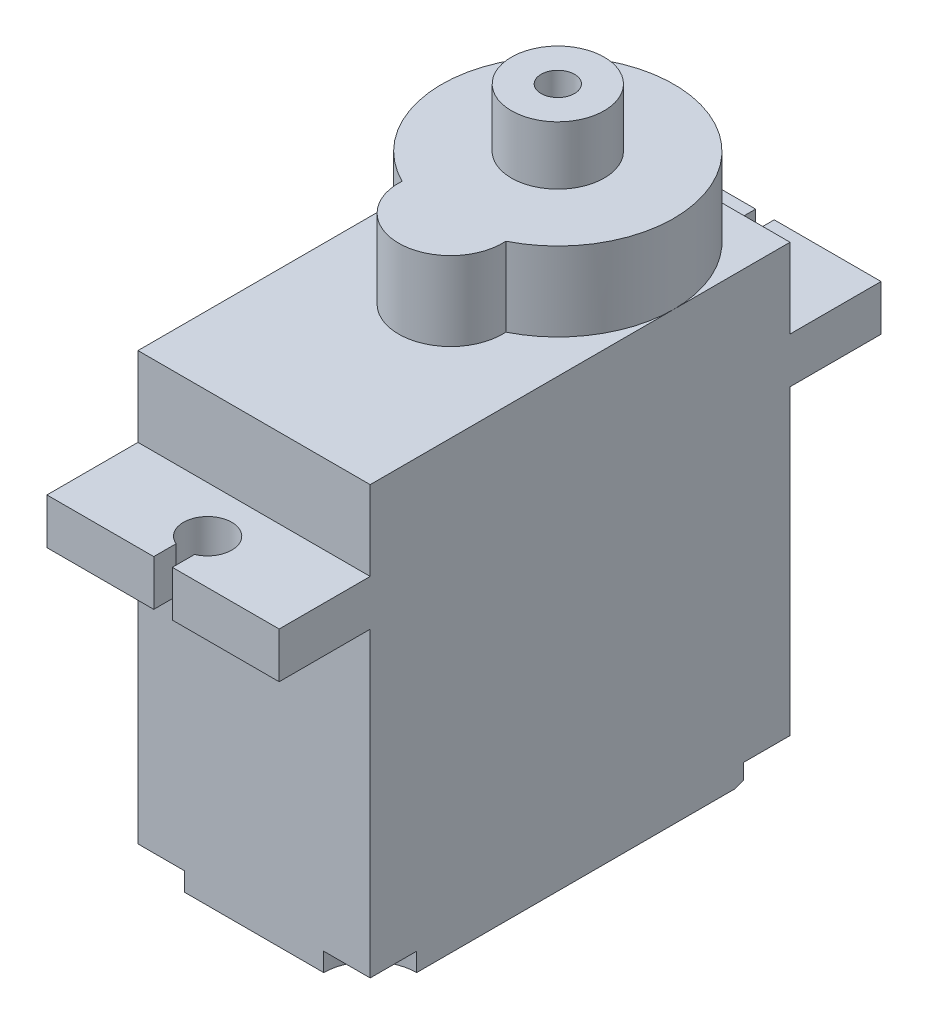
SolidWorks part; units mm, degrees
ref_plane "前视基准面" through (0, 0, 0) normal (0, 0, 1) x (1, 0, 0)
ref_plane "上视基准面" through (0, 0, 0) normal (0, 1, 0) x (1, 0, 0)
ref_plane "右视基准面" through (0, 0, 0) normal (1, 0, 0) x (0, 0, -1)
sketch "草图1" plane through (0, 0, 0) normal (1, 0, 0) x (0, 0, -1)
  line L0 (0, 19.5421) -> (0, -20.1589) construction
  line L1 (-21.5047, 0) -> (24.8692, 0) construction
  line L2 (-11.3, 4.28) -> (11.3, 4.28)
  line L3 (-11.3, 4.28) -> (-11.3, 0)
  line L4 (-11.3, -19.72) -> (11.3, -19.72)
  line L5 (11.3, 4.28) -> (11.3, 0)
  line L6 (-11.3, -2.46) -> (-11.3, -19.72)
  line L7 (-11.3, 0) -> (-16.2, 0)
  line L9 (-11.3, -2.46) -> (-16.2, -2.46)
  line L10 (-16.2, 0) -> (-16.2, -2.46)
  line L11 (11.3, 0) -> (16.2, 0)
  line L13 (11.3, -2.46) -> (16.2, -2.46)
  line L14 (16.2, 0) -> (16.2, -2.46)
  line L15 (11.3, -2.46) -> (11.3, -19.72)
  dimension "D1" = 24
  dimension "D2" = 22.6
  dimension "D3" = 32.4
  dimension "D4" = 2.46
  dimension "D5" = 6.74
extrude "凸台-拉伸1" add sketch "草图1" along normal mid plane 12.5
sketch "草图2" plane through (0, 0, 0) normal (0, 1, 0) x (1, 0, 0)
  line L0 (0, 19.6844) -> (0, -18.8436) construction
  line L1 (-16.1248, 0) -> (17.1198, 0) construction
  line L2 (6.25, 16.2) -> (-6.25, 16.2) construction
  line L4 (-0.5, 15) -> (-0.5, 16.2)
  line L5 (-0.5, 16.2) -> (0.5, 16.2)
  line L6 (0.5, 15) -> (0.5, 16.2)
  line L7 (-0.5, -15) -> (-0.5, -16.2)
  line L8 (-0.5, -16.2) -> (0.5, -16.2)
  line L9 (0.5, -15) -> (0.5, -16.2)
  arc A0 (-0.5, 15) -> (0.5, 15) centre (0, 13.8) ccw
  arc A1 (-0.5, -15) -> (0.5, -15) centre (0, -13.8) cw
  point P4 (0, 12.5)
  dimension "D1" = 2.6
  dimension "D3" = 12.5
  dimension "D2" = 1
extrude "切除-拉伸1" cut sketch "草图2" against normal blind 12.5
sketch "草图3" plane through (0, 4.28, 0) normal (0, 1, 0) x (1, 0, 0)
  line L0 (6.25, 11.3) -> (6.25, -11.3) construction
  line L1 (-6.25, 11.3) -> (-6.25, -11.3) construction
  line L2 (6.25, 11.3) -> (-6.25, 11.3) construction
  line L3 (0, 20.5537) -> (0, -26.165) construction
  line L4 (-6.25, 11.3) -> (6.25, 11.3) construction
  line L5 (-8.8354, -3.52) -> (12.7267, -3.52) construction
  arc A0 (2.7942, -0.5406) -> (-2.7942, -0.5406) centre (0, 5.05) ccw
  arc A1 (-2.7942, -0.5406) -> (2.7942, -0.5406) centre (0, -0.72) ccw
  dimension "D1" = 5.6
  dimension "D2" = 14.82
extrude "凸台-拉伸2" add sketch "草图3" along normal blind 4.24
sketch "草图4" plane through (0, 8.52, 0) normal (0, 1, 0) x (1, 0, 0)
  circle A0 centre (0, 5.05) radius 2.5
  circle A1 centre (0, 5.05) radius 0.9
  arc A2 (2.7942, -0.5406) -> (6.25, 5.05) centre (0, 5.05) ccw construction
  dimension "D1" = 5
  dimension "D2" = 1.8
extrude "凸台-拉伸3" add sketch "草图4" along normal blind 3.14
sketch "草图5" plane through (0, -19.72, 0) normal (0, -1, 0) x (1, 0, 0)
  line L0 (-10.9246, 0) -> (15.057, 0) construction
  line L1 (0, 16.6396) -> (0, -18.7058) construction
  circle A0 centre (6.25, 11.3) radius 2.5
  circle A1 centre (6.25, -11.3) radius 2.5
  circle A2 centre (-6.25, -11.3) radius 2.5
  circle A3 centre (-6.25, 11.3) radius 2.5
  dimension "D1" = 5
extrude "切除-拉伸2" cut sketch "草图5" against normal blind 1
sketch "草图6" plane through (-6.25, 0, 0) normal (-1, 0, 0) x (0, 0, 1)
  line L0 (-11.3, -18.72) -> (-11.3, -19.72)
  line L1 (-11.3, -18.72) -> (-11.3, -2.46) construction
  line L2 (-11.3, -19.72) -> (-8.3, -19.72)
  line L3 (8.8, -19.72) -> (-8.8, -19.72) construction
  line L4 (-8.3, -19.72) -> (-11.3, -18.72)
  dimension "D1" = 3
  dimension "D2" = 1
extrude "切除-拉伸3" cut sketch "草图6" against normal up to surface (12.5 mm away) up to face at (6.25, -6.5482, -0.2971)
sketch "定位线" plane through (0, 11.66, 0) normal (0, 1, 0) x (1, 0, 0)
  line L0 (0, 5.05) -> (-5, 5.05) construction
  line L1 (0, 5.05) -> (0, 10.05) construction
  dimension "D1" = 5
  dimension "D2" = 5
